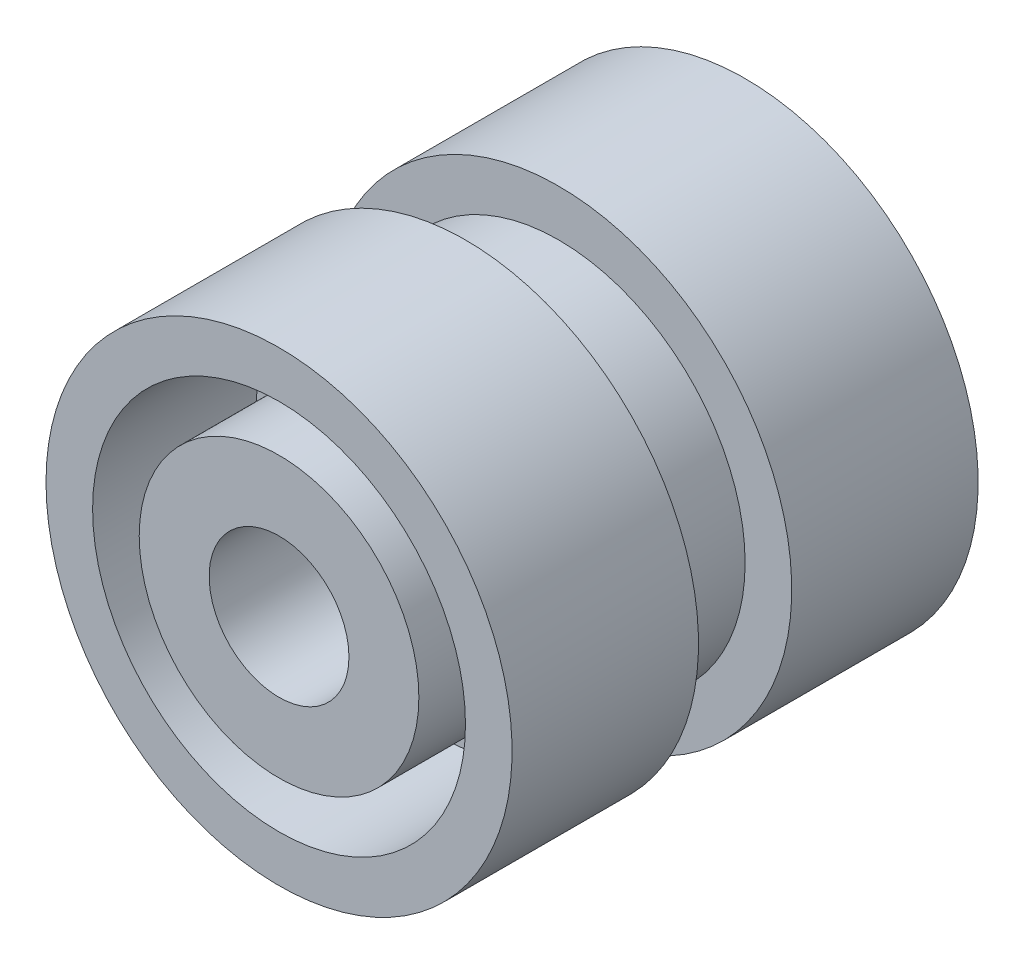
SolidWorks part; units mm, degrees
ref_plane "Front Plane" through (0, 0, 0) normal (0, 0, 1) x (1, 0, 0)
ref_plane "Top Plane" through (0, 0, 0) normal (0, 1, 0) x (1, 0, 0)
ref_plane "Right Plane" through (0, 0, 0) normal (1, 0, 0) x (0, 0, -1)
sketch "Sketch2" plane through (0, 0, 0) normal (1, 0, 0) x (0, 0, -1)
  line L0 (0, 0) -> (-6.4167, 0) construction
  line L1 (0, 0) -> (-5, 0)
  line L2 (-5, 0) -> (-5, 3)
  line L3 (-5, 3) -> (-1.5, 3)
  line L4 (-1.5, 3) -> (-1.5, 4)
  line L5 (-1.5, 4) -> (-5, 4)
  line L6 (-5, 4) -> (-5, 5)
  line L7 (-5, 5) -> (-1, 5)
  line L8 (-1, 5) -> (-1, 4)
  line L9 (-1, 4) -> (1, 4)
  line L10 (0, 4) -> (0, 0) construction
  line L11 (1, 5) -> (1, 4)
  line L12 (5, 5) -> (1, 5)
  line L13 (5, 4) -> (5, 5)
  line L14 (1.5, 4) -> (5, 4)
  line L15 (1.5, 4) -> (1.5, 0)
  line L16 (1.5, 0) -> (0, 0)
  point P18 (-13.9145, 3.7675)
  dimension "D1" = 5
  dimension "D2" = 3
  dimension "D3" = 3.5
  dimension "D4" = 1
  dimension "D5" = 3.5
  dimension "D6" = 1
  dimension "D7" = 1
  dimension "D8" = 1
  dimension "D9" = 4
revolve "Revolve1" add sketch "Sketch2" angle 360 about L0
sketch "Sketch3" plane through (0, 0, -1.5) normal (0, 0, -1) x (-1, 0, 0)
  line L0 (0, 0) -> (0, 4) construction
  line L1 (0.5, 1.9365) -> (0.5, 3.9686)
  line L2 (-0.5, 1.9365) -> (-0.5, 3.9686)
  line L3 (1.9365, 0.5) -> (3.9686, 0.5)
  line L4 (-0.5, 0) -> (-0.5, 4) construction
  line L5 (0.5, 0) -> (0.5, 4) construction
  line L6 (1.9365, -0.5) -> (3.9686, -0.5)
  line L7 (0.5, -1.9365) -> (0.5, -3.9686)
  line L8 (-0.5, -1.9365) -> (-0.5, -3.9686)
  line L9 (-1.9365, -0.5) -> (-3.9686, -0.5)
  line L10 (-1.9365, 0.5) -> (-3.9686, 0.5)
  arc A0 (-0.5, 1.9365) -> (-1.9365, 0.5) centre (0, 0) ccw
  circle A1 centre (0, 0) radius 4 construction
  arc A2 (-1.9365, -0.5) -> (-0.5, -1.9365) centre (0, 0) ccw
  arc A3 (1.9365, 0.5) -> (0.5, 1.9365) centre (0, 0) ccw
  arc A4 (0.5, -1.9365) -> (1.9365, -0.5) centre (0, 0) ccw
  circle A5 centre (0, 0) radius 4 construction
  circle A6 centre (0, 0) radius 4
  circle A7 centre (0, 0) radius 4
  point P28 (0, 0)
  circle M12 centre (0, 0) radius 4
  dimension "D1" = 4
  dimension "D2" = 0.5
  dimension "D3" = 0.5
  dimension "D4" = 4
extrude "Boss-Extrude1" add sketch "Sketch3" along normal blind 2 contours L7 A4 L6 L3 A3 L1 L2 A0 L10 L9 A2 L8 M12
sketch "Sketch4" plane through (0, 0, 5) normal (0, 0, 1) x (1, 0, 0)
  circle A0 centre (0, 0) radius 1.5
  dimension "D1" = 3
extrude "Cut-Extrude1" cut sketch "Sketch4" against normal blind 8
